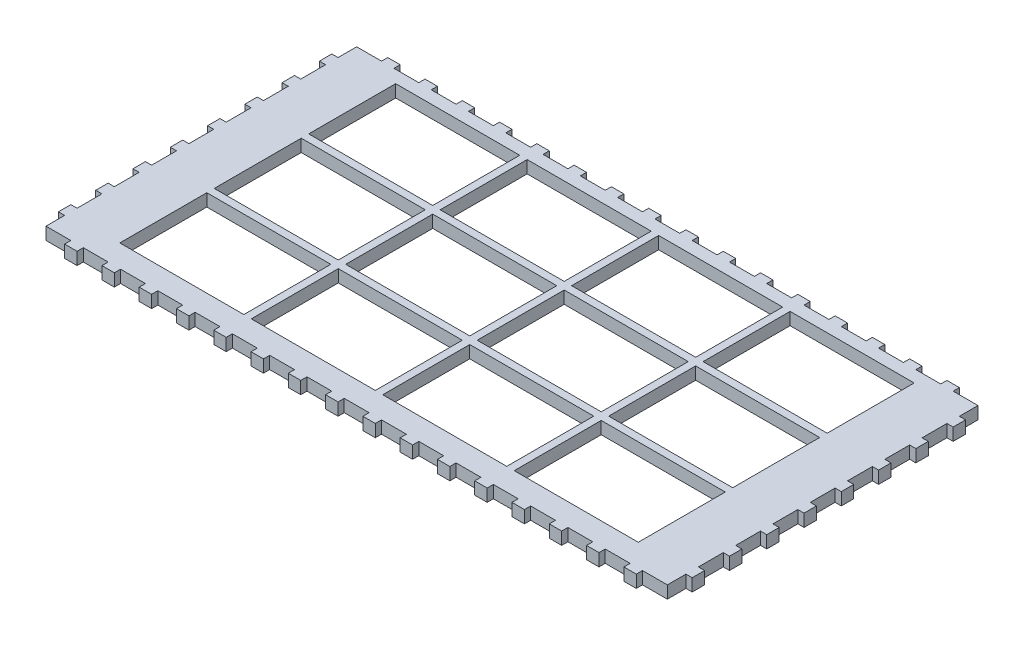
SolidWorks part; units mm, degrees
ref_plane "Front Plane" through (0, 0, 0) normal (0, 0, 1) x (1, 0, 0)
ref_plane "Top Plane" through (0, 0, 0) normal (0, 1, 0) x (1, 0, 0)
ref_plane "Right Plane" through (0, 0, 0) normal (1, 0, 0) x (0, 0, -1)
sketch "Sketch7" plane through (0, 0, 0) normal (0, 1, 0) x (1, 0, 0)
  line L0 (-3.81, 146.05) -> (-3.81, 57.15)
  line L1 (317.5, 158.75) -> (-317.5, 158.75)
  line L2 (317.5, 158.75) -> (317.5, -158.75)
  line L3 (317.5, -158.75) -> (-317.5, -158.75)
  line L4 (-317.5, 158.75) -> (-317.5, -158.75)
  line L5 (0, -158.75) -> (0, 158.75) construction
  line L6 (317.5, 0) -> (-317.5, 0) construction
  line L7 (-138.176, 146.05) -> (-264.922, 146.05)
  line L8 (-138.176, 146.05) -> (-138.176, 57.15)
  line L9 (-138.176, 57.15) -> (-264.922, 57.15)
  line L10 (-264.922, 146.05) -> (-264.922, 57.15)
  line L11 (-201.549, 57.15) -> (-201.549, 146.05) construction
  line L12 (-138.176, 101.6) -> (-264.922, 101.6) construction
  line L13 (-3.81, 57.15) -> (-130.556, 57.15)
  line L14 (-130.556, 146.05) -> (-130.556, 57.15)
  line L15 (-3.81, 146.05) -> (-130.556, 146.05)
  line L16 (130.556, 146.05) -> (130.556, 57.15)
  line L17 (130.556, 57.15) -> (3.81, 57.15)
  line L18 (3.81, 146.05) -> (3.81, 57.15)
  line L19 (130.556, 146.05) -> (3.81, 146.05)
  line L20 (-138.176, -46.99) -> (-138.176, -135.89)
  line L21 (-138.176, -135.89) -> (-264.922, -135.89)
  line L22 (-264.922, -46.99) -> (-264.922, -135.89)
  line L23 (-138.176, -46.99) -> (-264.922, -46.99)
  line L24 (-3.81, -46.99) -> (-3.81, -135.89)
  line L25 (-3.81, -135.89) -> (-130.556, -135.89)
  line L26 (-130.556, -46.99) -> (-130.556, -135.89)
  line L27 (-3.81, -46.99) -> (-130.556, -46.99)
  line L28 (130.556, -46.99) -> (130.556, -135.89)
  line L29 (130.556, -135.89) -> (3.81, -135.89)
  line L30 (3.81, -46.99) -> (3.81, -135.89)
  line L31 (130.556, -46.99) -> (3.81, -46.99)
  line L32 (-3.81, 49.53) -> (-3.81, -39.37)
  line L33 (-3.81, -39.37) -> (-130.556, -39.37)
  line L34 (-130.556, 49.53) -> (-130.556, -39.37)
  line L35 (-3.81, 49.53) -> (-130.556, 49.53)
  line L36 (130.556, 49.53) -> (130.556, -39.37)
  line L37 (130.556, -39.37) -> (3.81, -39.37)
  line L38 (3.81, 49.53) -> (3.81, -39.37)
  line L39 (130.556, 49.53) -> (3.81, 49.53)
  line L40 (264.922, 146.05) -> (264.922, 57.15)
  line L41 (264.922, 57.15) -> (138.176, 57.15)
  line L42 (138.176, 146.05) -> (138.176, 57.15)
  line L43 (264.922, 146.05) -> (138.176, 146.05)
  line L44 (264.922, 49.53) -> (264.922, -39.37)
  line L45 (264.922, -39.37) -> (138.176, -39.37)
  line L46 (138.176, 49.53) -> (138.176, -39.37)
  line L47 (264.922, 49.53) -> (138.176, 49.53)
  line L48 (264.922, -46.99) -> (264.922, -135.89)
  line L49 (264.922, -135.89) -> (138.176, -135.89)
  line L50 (138.176, -46.99) -> (138.176, -135.89)
  line L51 (264.922, -46.99) -> (138.176, -46.99)
  line L52 (-138.176, 49.53) -> (-138.176, -39.37)
  line L53 (-138.176, -39.37) -> (-264.922, -39.37)
  line L54 (-264.922, 49.53) -> (-264.922, -39.37)
  line L55 (-138.176, 49.53) -> (-264.922, 49.53)
  line L56 (-317.5, 146.05) -> (-264.922, 146.05) construction
  line L57 (370.078, 146.05) -> (317.5, 146.05) construction
  line L58 (-317.5, 29.9827) -> (-264.922, 29.9827) construction
  line L61 (264.922, 23.22) -> (317.5, 23.22) construction
  line L78 (-264.922, 146.05) -> (-317.5, 146.05) construction
  line L81 (-138.176, 57.15) -> (-138.176, 23.22) construction
  line L82 (-264.922, 146.05) -> (-264.922, 158.75) construction
  point P0 (0, 0)
  point P4 (-201.549, 101.6)
  dimension "D1" = 126.746
  dimension "D3" = 317.5
  dimension "D6" = 7.62
  dimension "D7" = 12.7
  dimension "D8" = 7.62
  dimension "D9" = 635
  dimension "D11" = 88.9
  dimension "D4" = 4
  dimension "D5" = 3
extrude "Boss-Extrude4" add sketch "Sketch7" along normal blind 12.7
sketch "Sketch8" plane through (0, 0, 0) normal (0, 1, 0) x (1, 0, 0)
  line L0 (-292.1, 158.75) -> (-292.1, 165.1)
  line L1 (-292.1, 165.1) -> (-279.4, 165.1)
  line L2 (-279.4, 165.1) -> (-279.4, 158.75)
  line L3 (317.5, 158.75) -> (-317.5, 158.75) construction
  line L4 (-292.1, 158.75) -> (-279.4, 158.75)
  line L29 (12.7, 165.1) -> (25.4, 165.1)
  line L58 (-317.5, 139.7) -> (-323.85, 139.7)
  line L59 (-317.5, 158.75) -> (-317.5, -158.75) construction
  line L60 (-323.85, 139.7) -> (-323.85, 127)
  line L61 (-323.85, 127) -> (-317.5, 127)
  line L62 (-317.5, 139.7) -> (-317.5, 127)
  line L63 (-323.85, 88.9) -> (-317.5, 88.9)
  line L64 (-317.5, 101.6) -> (-317.5, 88.9)
  line L65 (-317.5, 101.6) -> (-323.85, 101.6)
  line L66 (-323.85, 101.6) -> (-323.85, 88.9)
  line L67 (-323.85, 50.8) -> (-317.5, 50.8)
  line L68 (-317.5, 63.5) -> (-317.5, 50.8)
  line L69 (-317.5, 63.5) -> (-323.85, 63.5)
  line L70 (-323.85, 63.5) -> (-323.85, 50.8)
  line L71 (-323.85, 12.7) -> (-317.5, 12.7)
  line L72 (-317.5, 25.4) -> (-317.5, 12.7)
  line L73 (-317.5, 25.4) -> (-323.85, 25.4)
  line L74 (-323.85, 25.4) -> (-323.85, 12.7)
  line L75 (-323.85, -25.4) -> (-317.5, -25.4)
  line L76 (-317.5, -12.7) -> (-317.5, -25.4)
  line L77 (-317.5, -12.7) -> (-323.85, -12.7)
  line L78 (-323.85, -12.7) -> (-323.85, -25.4)
  line L95 (-323.85, -63.5) -> (-317.5, -63.5)
  line L120 (-317.5, -50.8) -> (-317.5, -63.5)
  line L121 (-317.5, -50.8) -> (-323.85, -50.8)
  line L122 (-323.85, -50.8) -> (-323.85, -63.5)
  line L123 (-323.85, -101.6) -> (-317.5, -101.6)
  line L124 (-317.5, -88.9) -> (-317.5, -101.6)
  line L125 (-317.5, -88.9) -> (-323.85, -88.9)
  line L126 (-323.85, -88.9) -> (-323.85, -101.6)
  line L127 (-323.85, -139.7) -> (-317.5, -139.7)
  line L128 (-317.5, -127) -> (-317.5, -139.7)
  line L129 (-317.5, -127) -> (-323.85, -127)
  line L130 (-323.85, -127) -> (-323.85, -139.7)
  line L131 (-317.5, -158.75) -> (317.5, -158.75) construction
  line L132 (-254, 165.1) -> (-241.3, 165.1)
  line L133 (-241.3, 165.1) -> (-241.3, 158.75)
  line L134 (-254, 158.75) -> (-241.3, 158.75)
  line L135 (-254, 158.75) -> (-254, 165.1)
  line L136 (-215.9, 165.1) -> (-203.2, 165.1)
  line L137 (-203.2, 165.1) -> (-203.2, 158.75)
  line L138 (-215.9, 158.75) -> (-203.2, 158.75)
  line L139 (-215.9, 158.75) -> (-215.9, 165.1)
  line L140 (-177.8, 165.1) -> (-165.1, 165.1)
  line L141 (-165.1, 165.1) -> (-165.1, 158.75)
  line L142 (-177.8, 158.75) -> (-165.1, 158.75)
  line L143 (-177.8, 158.75) -> (-177.8, 165.1)
  line L144 (-139.7, 165.1) -> (-127, 165.1)
  line L145 (-127, 165.1) -> (-127, 158.75)
  line L146 (-139.7, 158.75) -> (-127, 158.75)
  line L147 (-139.7, 158.75) -> (-139.7, 165.1)
  line L148 (-101.6, 165.1) -> (-88.9, 165.1)
  line L149 (-88.9, 165.1) -> (-88.9, 158.75)
  line L150 (-101.6, 158.75) -> (-88.9, 158.75)
  line L151 (-101.6, 158.75) -> (-101.6, 165.1)
  line L152 (-63.5, 165.1) -> (-50.8, 165.1)
  line L153 (-50.8, 165.1) -> (-50.8, 158.75)
  line L154 (-63.5, 158.75) -> (-50.8, 158.75)
  line L155 (-63.5, 158.75) -> (-63.5, 165.1)
  line L156 (-25.4, 165.1) -> (-12.7, 165.1)
  line L157 (-12.7, 165.1) -> (-12.7, 158.75)
  line L158 (-25.4, 158.75) -> (-12.7, 158.75)
  line L159 (-25.4, 158.75) -> (-25.4, 165.1)
  line L160 (-44.45, 139.7) -> (-50.8, 139.7) [skipped]
  line L161 (-50.8, 139.7) -> (-50.8, 127) [skipped]
  line L162 (-50.8, 127) -> (-44.45, 127) [skipped]
  line L163 (-44.45, 139.7) -> (-44.45, 127) [skipped]
  line L164 (-50.8, 88.9) -> (-44.45, 88.9) [skipped]
  line L165 (-44.45, 101.6) -> (-44.45, 88.9) [skipped]
  line L166 (-44.45, 101.6) -> (-50.8, 101.6) [skipped]
  line L167 (-50.8, 101.6) -> (-50.8, 88.9) [skipped]
  line L168 (-50.8, 50.8) -> (-44.45, 50.8) [skipped]
  line L169 (-44.45, 63.5) -> (-44.45, 50.8) [skipped]
  line L170 (-44.45, 63.5) -> (-50.8, 63.5) [skipped]
  line L171 (-50.8, 63.5) -> (-50.8, 50.8) [skipped]
  line L172 (-50.8, 12.7) -> (-44.45, 12.7) [skipped]
  line L173 (-44.45, 25.4) -> (-44.45, 12.7) [skipped]
  line L174 (-44.45, 25.4) -> (-50.8, 25.4) [skipped]
  line L175 (-50.8, 25.4) -> (-50.8, 12.7) [skipped]
  line L176 (-50.8, -25.4) -> (-44.45, -25.4) [skipped]
  line L177 (-44.45, -12.7) -> (-44.45, -25.4) [skipped]
  line L178 (-44.45, -12.7) -> (-50.8, -12.7) [skipped]
  line L179 (-50.8, -12.7) -> (-50.8, -25.4) [skipped]
  line L180 (25.4, 165.1) -> (25.4, 158.75)
  line L181 (12.7, 158.75) -> (25.4, 158.75)
  line L182 (12.7, 158.75) -> (12.7, 165.1)
  line L183 (50.8, 165.1) -> (63.5, 165.1)
  line L184 (63.5, 165.1) -> (63.5, 158.75)
  line L185 (50.8, 158.75) -> (63.5, 158.75)
  line L186 (50.8, 158.75) -> (50.8, 165.1)
  line L187 (88.9, 165.1) -> (101.6, 165.1)
  line L188 (101.6, 165.1) -> (101.6, 158.75)
  line L189 (88.9, 158.75) -> (101.6, 158.75)
  line L190 (88.9, 158.75) -> (88.9, 165.1)
  line L191 (127, 165.1) -> (139.7, 165.1)
  line L192 (139.7, 165.1) -> (139.7, 158.75)
  line L193 (127, 158.75) -> (139.7, 158.75)
  line L194 (127, 158.75) -> (127, 165.1)
  line L195 (165.1, 165.1) -> (177.8, 165.1)
  line L196 (177.8, 165.1) -> (177.8, 158.75)
  line L197 (165.1, 158.75) -> (177.8, 158.75)
  line L198 (165.1, 158.75) -> (165.1, 165.1)
  line L199 (203.2, 165.1) -> (215.9, 165.1)
  line L200 (215.9, 165.1) -> (215.9, 158.75)
  line L201 (203.2, 158.75) -> (215.9, 158.75)
  line L202 (203.2, 158.75) -> (203.2, 165.1)
  line L203 (241.3, 165.1) -> (254, 165.1)
  line L204 (254, 165.1) -> (254, 158.75)
  line L205 (241.3, 158.75) -> (254, 158.75)
  line L206 (241.3, 158.75) -> (241.3, 165.1)
  line L207 (279.4, 165.1) -> (292.1, 165.1)
  line L208 (292.1, 165.1) -> (292.1, 158.75)
  line L209 (279.4, 158.75) -> (292.1, 158.75)
  line L210 (279.4, 158.75) -> (279.4, 165.1)
  line L211 (317.5, -158.75) -> (317.5, 158.75) construction
  line L212 (-317.5, -158.75) -> (317.5, 158.75) construction
  line L213 (0, 0) -> (317.5, 0) construction
  line L214 (0, 0) -> (0, -158.75) construction
  line L215 (323.85, -127) -> (323.85, -139.7)
  line L216 (317.5, -127) -> (323.85, -127)
  line L217 (317.5, -127) -> (317.5, -139.7)
  line L218 (323.85, -139.7) -> (317.5, -139.7)
  line L219 (323.85, -88.9) -> (323.85, -101.6)
  line L220 (317.5, -88.9) -> (323.85, -88.9)
  line L221 (317.5, -88.9) -> (317.5, -101.6)
  line L222 (323.85, -101.6) -> (317.5, -101.6)
  line L223 (323.85, -50.8) -> (323.85, -63.5)
  line L224 (317.5, -50.8) -> (323.85, -50.8)
  line L225 (317.5, -50.8) -> (317.5, -63.5)
  line L226 (323.85, -63.5) -> (317.5, -63.5)
  line L227 (323.85, -12.7) -> (323.85, -25.4)
  line L228 (317.5, -12.7) -> (323.85, -12.7)
  line L229 (317.5, -12.7) -> (317.5, -25.4)
  line L230 (323.85, -25.4) -> (317.5, -25.4)
  line L231 (323.85, 25.4) -> (323.85, 12.7)
  line L232 (317.5, 25.4) -> (323.85, 25.4)
  line L233 (317.5, 25.4) -> (317.5, 12.7)
  line L234 (323.85, 12.7) -> (317.5, 12.7)
  line L235 (323.85, 63.5) -> (323.85, 50.8)
  line L236 (317.5, 63.5) -> (323.85, 63.5)
  line L237 (317.5, 63.5) -> (317.5, 50.8)
  line L238 (323.85, 50.8) -> (317.5, 50.8)
  line L239 (323.85, 101.6) -> (323.85, 88.9)
  line L240 (317.5, 101.6) -> (323.85, 101.6)
  line L241 (317.5, 101.6) -> (317.5, 88.9)
  line L242 (323.85, 88.9) -> (317.5, 88.9)
  line L243 (317.5, 139.7) -> (317.5, 127)
  line L244 (323.85, 127) -> (317.5, 127)
  line L245 (323.85, 139.7) -> (323.85, 127)
  line L246 (317.5, 139.7) -> (323.85, 139.7)
  line L247 (279.4, -158.75) -> (279.4, -165.1)
  line L248 (279.4, -158.75) -> (292.1, -158.75)
  line L249 (292.1, -165.1) -> (292.1, -158.75)
  line L250 (279.4, -165.1) -> (292.1, -165.1)
  line L251 (241.3, -158.75) -> (241.3, -165.1)
  line L252 (241.3, -158.75) -> (254, -158.75)
  line L253 (254, -165.1) -> (254, -158.75)
  line L254 (241.3, -165.1) -> (254, -165.1)
  line L255 (203.2, -158.75) -> (203.2, -165.1)
  line L256 (203.2, -158.75) -> (215.9, -158.75)
  line L257 (215.9, -165.1) -> (215.9, -158.75)
  line L258 (203.2, -165.1) -> (215.9, -165.1)
  line L259 (165.1, -158.75) -> (165.1, -165.1)
  line L260 (165.1, -158.75) -> (177.8, -158.75)
  line L261 (177.8, -165.1) -> (177.8, -158.75)
  line L262 (165.1, -165.1) -> (177.8, -165.1)
  line L263 (127, -158.75) -> (127, -165.1)
  line L264 (127, -158.75) -> (139.7, -158.75)
  line L265 (139.7, -165.1) -> (139.7, -158.75)
  line L266 (127, -165.1) -> (139.7, -165.1)
  line L267 (88.9, -158.75) -> (88.9, -165.1)
  line L268 (88.9, -158.75) -> (101.6, -158.75)
  line L269 (101.6, -165.1) -> (101.6, -158.75)
  line L270 (88.9, -165.1) -> (101.6, -165.1)
  line L271 (50.8, -158.75) -> (50.8, -165.1)
  line L272 (50.8, -158.75) -> (63.5, -158.75)
  line L273 (63.5, -165.1) -> (63.5, -158.75)
  line L274 (50.8, -165.1) -> (63.5, -165.1)
  line L275 (12.7, -158.75) -> (12.7, -165.1)
  line L276 (12.7, -158.75) -> (25.4, -158.75)
  line L277 (25.4, -165.1) -> (25.4, -158.75)
  line L278 (-25.4, -158.75) -> (-25.4, -165.1)
  line L279 (-25.4, -158.75) -> (-12.7, -158.75)
  line L280 (-12.7, -165.1) -> (-12.7, -158.75)
  line L281 (-25.4, -165.1) -> (-12.7, -165.1)
  line L282 (-63.5, -158.75) -> (-63.5, -165.1)
  line L283 (-63.5, -158.75) -> (-50.8, -158.75)
  line L284 (-50.8, -165.1) -> (-50.8, -158.75)
  line L285 (-63.5, -165.1) -> (-50.8, -165.1)
  line L286 (-101.6, -158.75) -> (-101.6, -165.1)
  line L287 (-101.6, -158.75) -> (-88.9, -158.75)
  line L288 (-88.9, -165.1) -> (-88.9, -158.75)
  line L289 (-101.6, -165.1) -> (-88.9, -165.1)
  line L290 (-139.7, -158.75) -> (-139.7, -165.1)
  line L291 (-139.7, -158.75) -> (-127, -158.75)
  line L292 (-127, -165.1) -> (-127, -158.75)
  line L293 (-139.7, -165.1) -> (-127, -165.1)
  line L294 (-177.8, -158.75) -> (-177.8, -165.1)
  line L295 (-177.8, -158.75) -> (-165.1, -158.75)
  line L296 (-165.1, -165.1) -> (-165.1, -158.75)
  line L297 (-177.8, -165.1) -> (-165.1, -165.1)
  line L298 (-215.9, -158.75) -> (-215.9, -165.1)
  line L299 (-215.9, -158.75) -> (-203.2, -158.75)
  line L300 (-203.2, -165.1) -> (-203.2, -158.75)
  line L301 (-215.9, -165.1) -> (-203.2, -165.1)
  line L302 (-254, -158.75) -> (-254, -165.1)
  line L303 (-254, -158.75) -> (-241.3, -158.75)
  line L304 (-241.3, -165.1) -> (-241.3, -158.75)
  line L305 (-254, -165.1) -> (-241.3, -165.1)
  line L306 (12.7, -165.1) -> (25.4, -165.1)
  line L307 (-292.1, -158.75) -> (-279.4, -158.75)
  line L308 (-279.4, -165.1) -> (-279.4, -158.75)
  line L309 (-292.1, -165.1) -> (-279.4, -165.1)
  line L310 (-292.1, -158.75) -> (-292.1, -165.1)
  dimension "D1" = 12.7
  dimension "D2" = 6.35
  dimension "D3" = 25.4
  dimension "D4" = 16
  dimension "D5" = 25.4
  dimension "D6" = 25.4
  dimension "D8" = 19.05
  dimension "D12" = 19.05
  dimension "D13" = 25.4
  dimension "D9" = 8
extrude "Boss-Extrude5" add sketch "Sketch8" along normal blind 12.7
